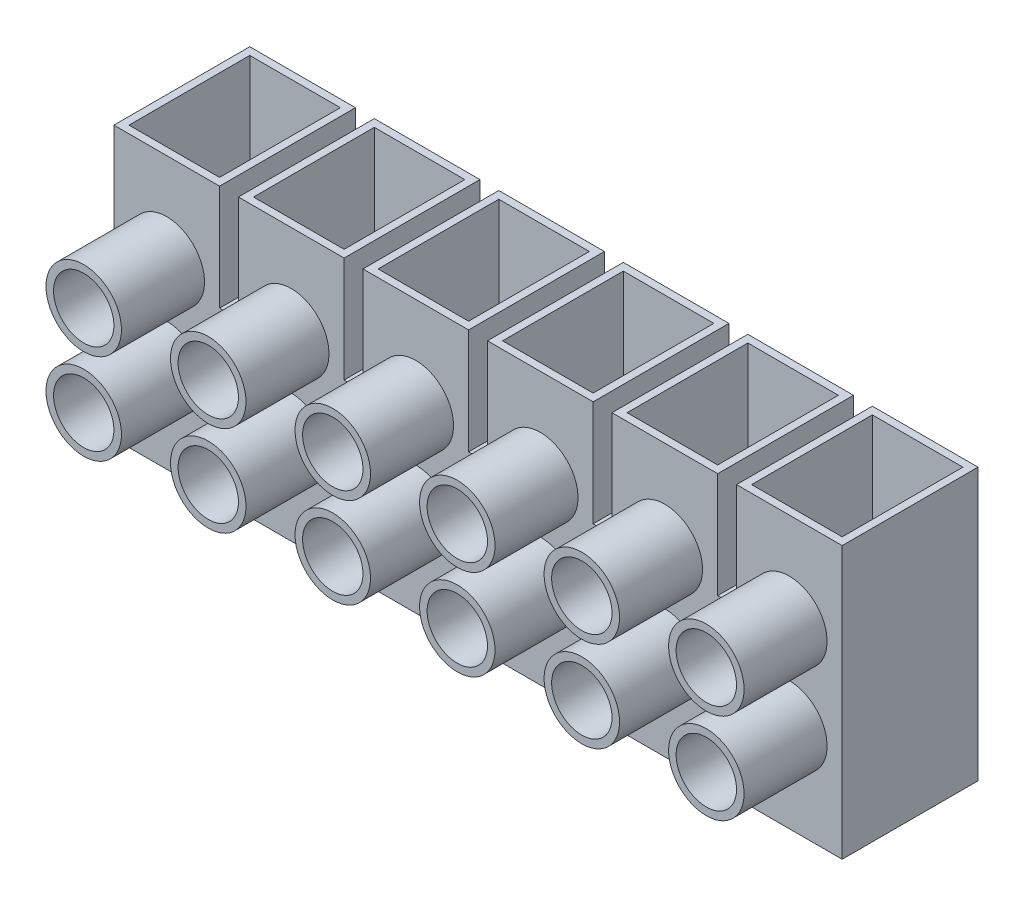
SolidWorks part; units mm, degrees
ref_plane "Alzado" through (0, 0, 0) normal (0, 0, 1) x (1, 0, 0)
ref_plane "Planta" through (0, 0, 0) normal (0, 1, 0) x (1, 0, 0)
ref_plane "Vista lateral" through (0, 0, 0) normal (1, 0, 0) x (0, 0, -1)
sketch "Croquis1" plane through (0, 0, 0) normal (0, 0, 1) x (1, 0, 0)
  line L0 (8.25, 0) -> (15.25, 0)
  line L1 (0, 0) -> (7, 0)
  line L2 (0, 0) -> (0, 18)
  line L3 (0, 18) -> (7, 18)
  line L4 (7, 0) -> (7, 18)
  line L5 (15.25, 0) -> (15.25, 18)
  line L6 (8.25, 18) -> (15.25, 18)
  line L7 (8.25, 0) -> (8.25, 18)
  line L8 (16.5, 0) -> (23.5, 0)
  line L9 (23.5, 0) -> (23.5, 18)
  line L10 (16.5, 18) -> (23.5, 18)
  line L11 (16.5, 0) -> (16.5, 18)
  line L12 (24.75, 0) -> (31.75, 0)
  line L13 (31.75, 0) -> (31.75, 18)
  line L14 (24.75, 18) -> (31.75, 18)
  line L15 (24.75, 0) -> (24.75, 18)
  line L16 (33, 0) -> (40, 0)
  line L17 (40, 0) -> (40, 18)
  line L18 (33, 18) -> (40, 18)
  line L19 (33, 0) -> (33, 18)
  line L20 (41.25, 0) -> (48.25, 0)
  line L21 (48.25, 0) -> (48.25, 18)
  line L22 (41.25, 18) -> (48.25, 18)
  line L23 (41.25, 0) -> (41.25, 18)
  dimension "D1" = 7
  dimension "D2" = 18
  dimension "D3" = 6
extrude "Saliente-Extruir1" add sketch "Croquis1" along normal blind 9
sketch "Croquis2" plane through (0, 0, 0) normal (0, 0, 1) x (1, 0, 0)
  line L0 (0, 9) -> (48.25, 9) construction
  line L1 (0, 18) -> (0, 0) construction
  line L2 (48.25, 0) -> (48.25, 18) construction
  line L3 (0, 7) -> (48.25, 7)
  line L4 (0, 11) -> (48.25, 11)
  line L5 (0, 7) -> (0, 11)
  line L6 (48.25, 7) -> (48.25, 11)
  dimension "D1" = 2
  dimension "D2" = 2
extrude "Saliente-Extruir2" add sketch "Croquis2" along normal blind 9
sketch "Croquis3" plane through (0, 0, 9) normal (0, 0, 1) x (1, 0, 0)
  line L0 (0, 9) -> (48.25, 9) construction
  line L1 (0, 18) -> (0, 0) construction
  line L2 (48.25, 0) -> (48.25, 18) construction
  circle A0 centre (3.5, 12) radius 2.5
  circle A1 centre (3.5, 12) radius 2
  circle A2 centre (11.75, 12) radius 2.5
  circle A3 centre (11.75, 12) radius 2
  circle A4 centre (20, 12) radius 2.5
  circle A5 centre (20, 12) radius 2
  circle A6 centre (28.25, 12) radius 2.5
  circle A7 centre (28.25, 12) radius 2
  circle A8 centre (36.5, 12) radius 2.5
  circle A9 centre (36.5, 12) radius 2
  circle A10 centre (44.75, 12) radius 2.5
  circle A11 centre (44.75, 12) radius 2
  circle A12 centre (11.75, 6) radius 2.5
  circle A13 centre (11.75, 6) radius 2
  circle A14 centre (20, 6) radius 2.5
  circle A15 centre (20, 6) radius 2
  circle A16 centre (28.25, 6) radius 2.5
  circle A17 centre (28.25, 6) radius 2
  circle A18 centre (36.5, 6) radius 2.5
  circle A19 centre (36.5, 6) radius 2
  circle A20 centre (44.75, 6) radius 2.5
  circle A21 centre (44.75, 6) radius 2
  circle A22 centre (3.5, 6) radius 2.5
  circle A23 centre (3.5, 6) radius 2
  dimension "D1" = 3
  dimension "D2" = 3
  dimension "D3" = 3.5
  dimension "D4" = 3.5
  dimension "D5" = 5
  dimension "D6" = 4
  dimension "D7" = 6
  dimension "D8" = 2
extrude "Saliente-Extruir3" add sketch "Croquis3" along normal blind 5.5
sketch "Croquis4" plane through (0, 0, 9) normal (0, 0, 1) x (1, 0, 0)
  line L0 (0, 9) -> (48.25, 9) construction
  line L1 (0, 18) -> (0, 0) construction
  line L2 (48.25, 0) -> (48.25, 18) construction
  circle A0 centre (7.625, 9) radius 1
  circle A1 centre (15.875, 9) radius 1
  circle A2 centre (24.125, 9) radius 1
  circle A3 centre (32.375, 9) radius 1
  circle A4 centre (40.625, 9) radius 1
  dimension "D1" = 2
  dimension "D2" = 7.625
  dimension "D3" = 5
extrude "Cortar-Extruir1" cut sketch "Croquis4" against normal through all
sketch "Croquis5" plane through (0, 0, 0) normal (0, -1, 0) x (1, 0, 0)
  line L0 (0.5, 0.5) -> (6.5, 0.5)
  line L1 (0, 0) -> (7, 0) construction
  line L2 (0, 0) -> (0, 9) construction
  line L3 (0, 9) -> (7, 9) construction
  line L4 (7, 0) -> (7, 9) construction
  line L5 (6.5, 0.5) -> (6.5, 8.5)
  line L6 (0.5, 8.5) -> (6.5, 8.5)
  line L7 (0.5, 0.5) -> (0.5, 8.5)
  line L8 (8.75, 0.5) -> (14.75, 0.5)
  line L9 (8.75, 0.5) -> (8.75, 8.5)
  line L10 (8.75, 8.5) -> (14.75, 8.5)
  line L11 (14.75, 0.5) -> (14.75, 8.5)
  line L12 (17, 0.5) -> (23, 0.5)
  line L13 (17, 0.5) -> (17, 8.5)
  line L14 (17, 8.5) -> (23, 8.5)
  line L15 (23, 0.5) -> (23, 8.5)
  line L16 (25.25, 0.5) -> (31.25, 0.5)
  line L17 (25.25, 0.5) -> (25.25, 8.5)
  line L18 (25.25, 8.5) -> (31.25, 8.5)
  line L19 (31.25, 0.5) -> (31.25, 8.5)
  line L20 (33.5, 0.5) -> (39.5, 0.5)
  line L21 (33.5, 0.5) -> (33.5, 8.5)
  line L22 (33.5, 8.5) -> (39.5, 8.5)
  line L23 (39.5, 0.5) -> (39.5, 8.5)
  line L24 (41.75, 0.5) -> (47.75, 0.5)
  line L25 (41.75, 0.5) -> (41.75, 8.5)
  line L26 (41.75, 8.5) -> (47.75, 8.5)
  line L27 (47.75, 0.5) -> (47.75, 8.5)
  dimension "D1" = 0.5
  dimension "D2" = 6
extrude "Cortar-Extruir2" cut sketch "Croquis5" against normal through all
equation "\"D2@Croquis4\"=7+1.25/2"
